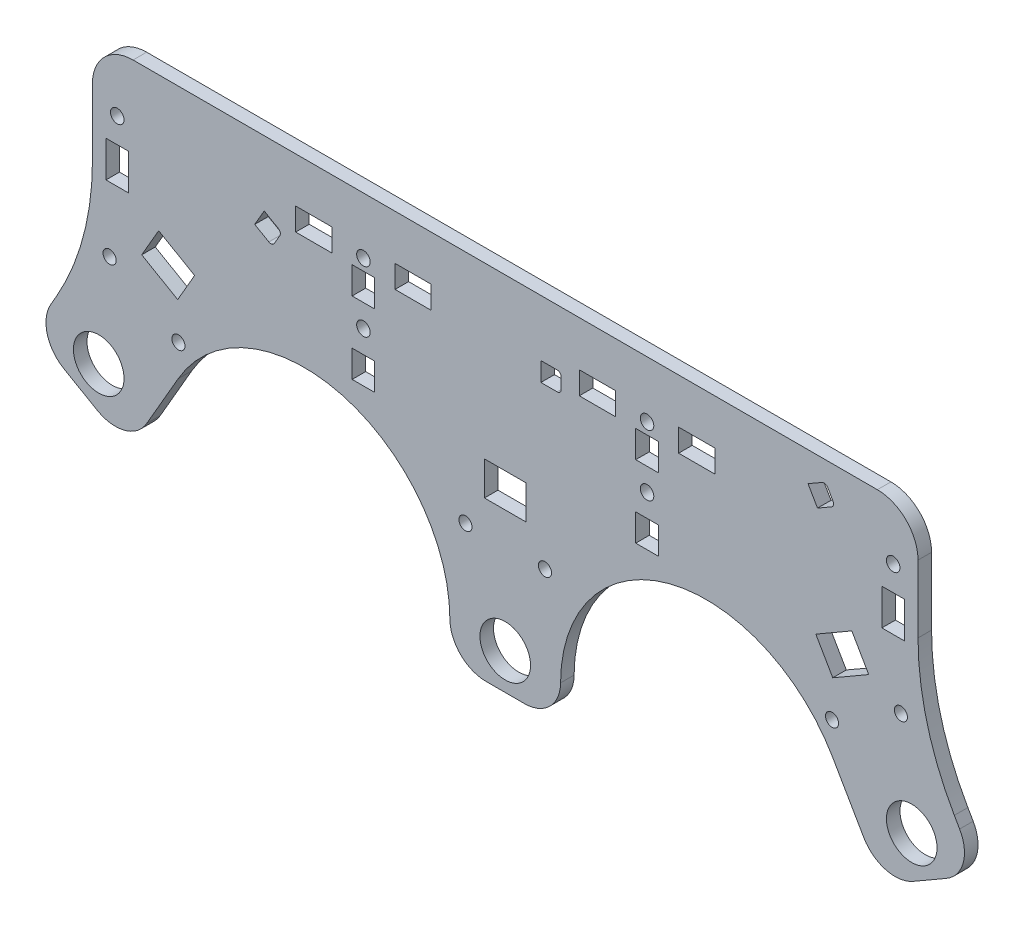
SolidWorks part; units mm, degrees
ref_plane "Front Plane" through (0, 0, 0) normal (0, 0, 1) x (1, 0, 0)
ref_plane "Top Plane" through (0, 0, 0) normal (0, 1, 0) x (1, 0, 0)
ref_plane "Right Plane" through (0, 0, 0) normal (1, 0, 0) x (0, 0, -1)
sketch "Sketch1" plane through (0, 0, 0) normal (0, 0, 1) x (1, 0, 0)
  line L0 (-12.25, 32.0854) -> (-12.25, -8)
  line L1 (-12.25, -8) -> (12.25, -8)
  line L2 (12.25, -8) -> (12.25, 32.0854)
  line L3 (12.25, 32.0854) -> (63.1039, 32.0854)
  line L4 (63.1039, 32.0854) -> (83.3912, -3.0532)
  line L5 (83.3912, -3.0532) -> (104.6088, 9.1968)
  line L6 (104.6088, 9.1968) -> (91.394, 32.0854)
  line L7 (91.394, 32.0854) -> (91.394, 72.0854)
  line L8 (91.394, 72.0854) -> (-91.394, 72.0854)
  line L9 (-91.394, 72.0854) -> (-91.394, 32.0854)
  line L10 (-91.394, 32.0854) -> (-104.6088, 9.1968)
  line L11 (-104.6088, 9.1968) -> (-83.3912, -3.0532)
  line L12 (-83.3912, -3.0532) -> (-63.1039, 32.0854)
  line L13 (-63.1039, 32.0854) -> (-12.25, 32.0854)
  line L14 (7.75, -12) -> (-7.75, -12) construction
  line L15 (102.7117, 3.4827) -> (89.2883, -4.2673) construction
  line L16 (-89.2883, -4.2673) -> (-102.7117, 3.4827) construction
  line L17 (-67.7572, 26.0256) -> (-84.5072, -2.9862) construction
  line L18 (-103.9928, 8.2638) -> (-87.2428, 37.2756) construction
  line L19 (87.2428, 37.2756) -> (103.9928, 8.2638) construction
  line L20 (84.5072, -2.9862) -> (67.7572, 26.0256) construction
  line L21 (11.25, 25) -> (11.25, -8.5) construction
  line L22 (-11.25, -8.5) -> (-11.25, 25) construction
  line L23 (-91.394, 32.0854) -> (-63.1039, 32.0854) construction
  line L24 (-12.25, 32.0854) -> (12.25, 32.0854) construction
  line L25 (63.1039, 32.0854) -> (91.394, 32.0854) construction
  line L26 (0, 72.0854) -> (0, -50.5753) construction
  circle A0 centre (0, 0) radius 33.5 construction
  circle A1 centre (-90, 10) radius 33.5 construction
  circle A2 centre (90, 10) radius 33.5 construction
  arc A3 (-72.4108, 15.9654) -> (-12.25, -0.1546) centre (-44.4901, -0.1546) cw
  arc A4 (72.4108, 15.9654) -> (12.25, -0.1546) centre (44.4901, -0.1546) ccw
  dimension "D10" = 67
  dimension "D11" = 40
  dimension "D1" = 4
  dimension "D2" = 4
  dimension "D3" = 4
  dimension "D4" = 1
  dimension "D5" = 1
  dimension "D6" = 1
  dimension "D7" = 1
  dimension "D8" = 1
  dimension "D9" = 1
extrude "Boss-Extrude1" add sketch "Sketch1" along normal blind 3 contours L12 L13 L0 L1 L2 L3 L4 L5 L6 L7 L8 L9 L10 L11 | L12 A3 L13 | L13 A3 L0 | A4 L3 L2 | A4 L4 L3
fillet "Fillet1" radius 60 2 edges at (91.394, 32.0854, 1.5) (-91.394, 32.0854, 1.5)
fillet "Fillet2" radius 8 6 edges at (-104.6088, 9.1968, 1.5) (-83.3912, -3.0532, 1.5) (-12.25, -8, 1.5) (12.25, -8, 1.5) (83.3912, -3.0532, 1.5) (104.6088, 9.1968, 1.5)
sketch "Sketch3" plane through (0, 0, 3) normal (0, 0, 1) x (1, 0, 0)
  line L8 (-53.3584, 57.6651) -> (-55.4584, 54.0278)
  line L9 (-55.4584, 54.0278) -> (-52.3407, 52.2278)
  line L10 (-51.1113, 52.5572) -> (-49.9113, 54.6357)
  line L11 (-50.2407, 55.8651) -> (-53.3584, 57.6651)
  line L12 (-53.3584, 57.6651) -> (-55.4584, 54.0278)
  line L13 (-55.4584, 54.0278) -> (-52.3407, 52.2278)
  line L14 (-51.1113, 52.5572) -> (-49.9113, 54.6357)
  line L15 (-50.2407, 55.8651) -> (-53.3584, 57.6651)
  line L16 (-68.7663, 37.5779) -> (-76.7337, 42.1779)
  line L17 (-76.7337, 42.1779) -> (-80.4837, 35.6827)
  line L18 (-80.4837, 35.6827) -> (-72.5163, 31.0827)
  line L19 (-72.5163, 31.0827) -> (-68.7663, 37.5779)
  line L20 (7.9, 59.6) -> (7.9, 55.4)
  line L21 (7.9, 55.4) -> (11.5, 55.4)
  line L22 (12.4, 56.3) -> (12.4, 58.7)
  line L23 (11.5, 59.6) -> (7.9, 59.6)
  line L24 (7.9, 59.6) -> (7.9, 55.4)
  line L25 (7.9, 55.4) -> (11.5, 55.4)
  line L26 (12.4, 56.3) -> (12.4, 58.7)
  line L27 (11.5, 59.6) -> (7.9, 59.6)
  line L32 (67.0416, 65.5651) -> (69.1416, 61.9278)
  line L33 (69.1416, 61.9278) -> (72.2593, 63.7278)
  line L34 (72.5887, 64.9572) -> (71.3887, 67.0357)
  line L35 (70.1593, 67.3651) -> (67.0416, 65.5651)
  line L36 (67.0416, 65.5651) -> (69.1416, 61.9278)
  line L37 (69.1416, 61.9278) -> (72.2593, 63.7278)
  line L38 (72.5887, 64.9572) -> (71.3887, 67.0357)
  line L39 (70.1593, 67.3651) -> (67.0416, 65.5651)
  line L40 (-68.7663, 37.5779) -> (-76.7337, 42.1779)
  line L41 (-76.7337, 42.1779) -> (-80.4837, 35.6827)
  line L42 (-80.4837, 35.6827) -> (-72.5163, 31.0827)
  line L43 (-72.5163, 31.0827) -> (-68.7663, 37.5779)
  line L48 (4.6, 34.5) -> (-4.6, 34.5)
  line L49 (-4.6, 34.5) -> (-4.6, 27)
  line L50 (-4.6, 27) -> (4.6, 27)
  line L51 (4.6, 27) -> (4.6, 34.5)
  line L52 (4.6, 34.5) -> (-4.6, 34.5)
  line L53 (-4.6, 34.5) -> (-4.6, 27)
  line L54 (-4.6, 27) -> (4.6, 27)
  line L55 (4.6, 27) -> (4.6, 34.5)
  line L60 (76.7337, 42.1779) -> (68.7663, 37.5779)
  line L61 (68.7663, 37.5779) -> (72.5163, 31.0827)
  line L62 (72.5163, 31.0827) -> (80.4837, 35.6827)
  line L63 (80.4837, 35.6827) -> (76.7337, 42.1779)
  line L64 (76.7337, 42.1779) -> (68.7663, 37.5779)
  line L65 (68.7663, 37.5779) -> (72.5163, 31.0827)
  line L66 (72.5163, 31.0827) -> (80.4837, 35.6827)
  line L67 (80.4837, 35.6827) -> (76.7337, 42.1779)
  circle A0 centre (87.596, 31.7638) radius 1.45 construction
  circle A1 centre (72.354, 22.9638) radius 1.45 construction
  circle A2 centre (8.8, 20.05) radius 1.45 construction
  circle A3 centre (-8.8, 20.05) radius 1.45 construction
  circle A4 centre (-87.596, 31.7638) radius 1.45 construction
  circle A5 centre (-72.354, 22.9638) radius 1.45 construction
  circle A6 centre (87.596, 31.7638) radius 1.45
  circle A7 centre (72.354, 22.9638) radius 1.45
  circle A8 centre (8.8, 20.05) radius 1.45
  circle A9 centre (-8.8, 20.05) radius 1.45
  circle A10 centre (-87.596, 31.7638) radius 1.45
  circle A11 centre (-72.354, 22.9638) radius 1.45
  circle A14 centre (-84.375, 19.7428) radius 3.45
  circle A15 centre (-84.375, 19.7428) radius 3.45 construction
  arc A16 (-52.3407, 52.2278) -> (-51.1113, 52.5572) centre (-51.8907, 53.0072) ccw
  arc A17 (-49.9113, 54.6357) -> (-50.2407, 55.8651) centre (-50.6907, 55.0857) ccw
  arc A18 (-52.3407, 52.2278) -> (-51.1113, 52.5572) centre (-51.8907, 53.0072) ccw
  arc A19 (-49.9113, 54.6357) -> (-50.2407, 55.8651) centre (-50.6907, 55.0857) ccw
  circle A21 centre (0, 11.25) radius 3.45
  arc A22 (11.5, 55.4) -> (12.4, 56.3) centre (11.5, 56.3) ccw
  arc A23 (12.4, 58.7) -> (11.5, 59.6) centre (11.5, 58.7) ccw
  arc A24 (11.5, 55.4) -> (12.4, 56.3) centre (11.5, 56.3) ccw
  arc A25 (12.4, 58.7) -> (11.5, 59.6) centre (11.5, 58.7) ccw
  circle A26 centre (0, 11.25) radius 3.45 construction
  arc A28 (72.2593, 63.7278) -> (72.5887, 64.9572) centre (71.8093, 64.5072) ccw
  arc A29 (71.3887, 67.0357) -> (70.1593, 67.3651) centre (70.6093, 66.5857) ccw
  arc A30 (72.2593, 63.7278) -> (72.5887, 64.9572) centre (71.8093, 64.5072) ccw
  arc A31 (71.3887, 67.0357) -> (70.1593, 67.3651) centre (70.6093, 66.5857) ccw
  circle A32 centre (84.375, 19.7428) radius 3.45
  circle A33 centre (84.375, 19.7428) radius 3.45 construction
  circle A35 centre (0, 0) radius 5.6
  circle A36 centre (0, 0) radius 5.6
  circle A38 centre (-90, 10) radius 5.6
  circle A39 centre (-90, 10) radius 5.6
  circle A41 centre (90, 10) radius 5.6
  circle A42 centre (90, 10) radius 5.6
  dimension "D1" = 0.1
  dimension "D2" = 0.1
  dimension "D3" = 0.1
  dimension "D4" = 2
  dimension "D5" = 2
  dimension "D6" = 2
  dimension "D7" = 1.5
  dimension "D8" = 1.5
  dimension "D9" = 1.5
  dimension "D10" = 2
  dimension "D11" = 2
  dimension "D12" = 2
extrude "Cut-Extrude1" cut sketch "Sketch3" against normal through all
sketch "Sketch4" plane through (0, 0, 3) normal (0, 0, 1) x (1, 0, 0)
  line L0 (84.394, 57.0854) -> (84.394, 62.0854) construction
  line L1 (29.894, 57.0854) -> (29.894, 62.0854) construction
  line L2 (32.894, 57.0854) -> (32.894, 62.0854) construction
  line L3 (87.394, 57.0854) -> (87.394, 62.0854) construction
  line L4 (-46.394, 62.0854) -> (-46.394, 57.0854)
  line L5 (-46.394, 57.0854) -> (-38.394, 57.0854)
  line L6 (-38.394, 57.0854) -> (-38.394, 62.0854)
  line L7 (-38.394, 62.0854) -> (-46.394, 62.0854)
  line L8 (-46.394, 62.0854) -> (-46.394, 57.0854)
  line L9 (-46.394, 57.0854) -> (-38.394, 57.0854)
  line L10 (-38.394, 57.0854) -> (-38.394, 62.0854)
  line L11 (-38.394, 62.0854) -> (-46.394, 62.0854)
  line L12 (-16.394, 57.0854) -> (-16.394, 62.0854)
  line L13 (-16.394, 62.0854) -> (-24.394, 62.0854)
  line L14 (-24.394, 62.0854) -> (-24.394, 57.0854)
  line L15 (-24.394, 57.0854) -> (-16.394, 57.0854)
  line L16 (-16.394, 57.0854) -> (-16.394, 62.0854)
  line L17 (-16.394, 62.0854) -> (-24.394, 62.0854)
  line L18 (-24.394, 62.0854) -> (-24.394, 57.0854)
  line L19 (-24.394, 57.0854) -> (-16.394, 57.0854)
  line L20 (16.394, 62.0854) -> (16.394, 57.0854)
  line L21 (16.394, 57.0854) -> (24.394, 57.0854)
  line L22 (24.394, 57.0854) -> (24.394, 62.0854)
  line L23 (24.394, 62.0854) -> (16.394, 62.0854)
  line L24 (16.394, 62.0854) -> (16.394, 57.0854)
  line L25 (16.394, 57.0854) -> (24.394, 57.0854)
  line L26 (24.394, 57.0854) -> (24.394, 62.0854)
  line L27 (24.394, 62.0854) -> (16.394, 62.0854)
  line L28 (46.394, 57.0854) -> (46.394, 62.0854)
  line L29 (46.394, 62.0854) -> (38.394, 62.0854)
  line L30 (38.394, 62.0854) -> (38.394, 57.0854)
  line L31 (38.394, 57.0854) -> (46.394, 57.0854)
  line L32 (46.394, 57.0854) -> (46.394, 62.0854)
  line L33 (46.394, 62.0854) -> (38.394, 62.0854)
  line L34 (38.394, 62.0854) -> (38.394, 57.0854)
  line L35 (38.394, 57.0854) -> (46.394, 57.0854)
  line L36 (-29.894, 57.0854) -> (-29.894, 62.0854) construction
  line L37 (-32.894, 57.0854) -> (-32.894, 62.0854) construction
  line L38 (-84.394, 57.0854) -> (-84.394, 62.0854) construction
  line L39 (-87.394, 57.0854) -> (-87.394, 62.0854) construction
  line L40 (-84.394, 57.0854) -> (-84.394, 62.0854) construction
  line L41 (-87.394, 57.0854) -> (-87.394, 62.0854) construction
  line L42 (84.394, 57.0854) -> (84.394, 62.0854) construction
  line L43 (-32.894, 57.0854) -> (-32.894, 62.0854) construction
  line L44 (-29.894, 57.0854) -> (-29.894, 62.0854) construction
  line L45 (87.394, 57.0854) -> (87.394, 62.0854) construction
  line L46 (32.894, 57.0854) -> (32.894, 62.0854) construction
  line L47 (29.894, 57.0854) -> (29.894, 62.0854) construction
  line L48 (-87.394, 59.5854) -> (-84.394, 59.5854) construction
  line L49 (-32.894, 59.5854) -> (-29.894, 59.5854) construction
  line L50 (29.894, 59.5854) -> (32.894, 59.5854) construction
  line L51 (84.394, 59.5854) -> (87.394, 59.5854) construction
  circle A0 centre (-31.394, 59.5854) radius 1.5
  circle A1 centre (31.394, 59.5854) radius 1.5
  circle A2 centre (-85.894, 59.5854) radius 1.5
  circle A3 centre (85.894, 59.5854) radius 1.5
  dimension "D1" = 0
  dimension "D2" = 0
  dimension "D3" = 0
  dimension "D4" = 0
extrude "Cut-Extrude2" cut sketch "Sketch4" against normal through all
sketch "Sketch5" plane through (0, 0, 3) normal (0, 0, 1) x (1, 0, 0)
  line L4 (-88.394, 54.0854) -> (-88.394, 46.0854)
  line L5 (-88.394, 46.0854) -> (-83.394, 46.0854)
  line L6 (-83.394, 46.0854) -> (-83.394, 54.0854)
  line L7 (-83.394, 54.0854) -> (-88.394, 54.0854)
  line L8 (-88.394, 54.0854) -> (-88.394, 46.0854)
  line L9 (-88.394, 46.0854) -> (-83.394, 46.0854)
  line L10 (-83.394, 46.0854) -> (-83.394, 54.0854)
  line L11 (-83.394, 54.0854) -> (-88.394, 54.0854)
  line L12 (88.394, 46.0854) -> (88.394, 54.0854)
  line L13 (88.394, 54.0854) -> (83.394, 54.0854)
  line L14 (83.394, 54.0854) -> (83.394, 46.0854)
  line L15 (83.394, 46.0854) -> (88.394, 46.0854)
  line L16 (88.394, 46.0854) -> (88.394, 54.0854)
  line L17 (88.394, 54.0854) -> (83.394, 54.0854)
  line L18 (83.394, 54.0854) -> (83.394, 46.0854)
  line L19 (83.394, 46.0854) -> (88.394, 46.0854)
  dimension "D1" = 0
  dimension "D2" = 0
extrude "Cut-Extrude3" cut sketch "Sketch5" against normal through all
fillet "Fillet3" radius 9 2 edges at (-91.394, 72.0854, 1.5) (91.394, 72.0854, 1.5)
sketch "Sketch6" plane through (0, 0, 3) normal (0, 0, 1) x (1, 0, 0)
  line L0 (-28.894, 44.5854) -> (-33.894, 44.5854) construction
  line L1 (-28.894, 47.5854) -> (-33.894, 47.5854) construction
  line L2 (28.894, 44.5854) -> (33.894, 44.5854) construction
  line L3 (28.894, 47.5854) -> (33.894, 47.5854) construction
  line L4 (33.894, 35.0854) -> (33.894, 41.0854)
  line L5 (33.894, 41.0854) -> (28.894, 41.0854)
  line L6 (28.894, 41.0854) -> (28.894, 35.0854)
  line L7 (28.894, 35.0854) -> (33.894, 35.0854)
  line L8 (33.894, 35.0854) -> (33.894, 41.0854)
  line L9 (33.894, 41.0854) -> (28.894, 41.0854)
  line L10 (28.894, 41.0854) -> (28.894, 35.0854)
  line L11 (28.894, 35.0854) -> (33.894, 35.0854)
  line L12 (33.894, 51.0854) -> (33.894, 57.0854)
  line L13 (33.894, 57.0854) -> (28.894, 57.0854)
  line L14 (28.894, 57.0854) -> (28.894, 51.0854)
  line L15 (28.894, 51.0854) -> (33.894, 51.0854)
  line L16 (33.894, 51.0854) -> (33.894, 57.0854)
  line L17 (33.894, 57.0854) -> (28.894, 57.0854)
  line L18 (28.894, 57.0854) -> (28.894, 51.0854)
  line L19 (28.894, 51.0854) -> (33.894, 51.0854)
  line L20 (-33.894, 57.0854) -> (-33.894, 51.0854)
  line L21 (-33.894, 51.0854) -> (-28.894, 51.0854)
  line L22 (-28.894, 51.0854) -> (-28.894, 57.0854)
  line L23 (-28.894, 57.0854) -> (-33.894, 57.0854)
  line L24 (-33.894, 57.0854) -> (-33.894, 51.0854)
  line L25 (-33.894, 51.0854) -> (-28.894, 51.0854)
  line L26 (-28.894, 51.0854) -> (-28.894, 57.0854)
  line L27 (-28.894, 57.0854) -> (-33.894, 57.0854)
  line L28 (-33.894, 41.0854) -> (-33.894, 35.0854)
  line L29 (-33.894, 35.0854) -> (-28.894, 35.0854)
  line L30 (-28.894, 35.0854) -> (-28.894, 41.0854)
  line L31 (-28.894, 41.0854) -> (-33.894, 41.0854)
  line L32 (-33.894, 41.0854) -> (-33.894, 35.0854)
  line L33 (-33.894, 35.0854) -> (-28.894, 35.0854)
  line L34 (-28.894, 35.0854) -> (-28.894, 41.0854)
  line L35 (-28.894, 41.0854) -> (-33.894, 41.0854)
  line L36 (-28.894, 44.5854) -> (-33.894, 44.5854) construction
  line L37 (-28.894, 47.5854) -> (-33.894, 47.5854) construction
  line L38 (28.894, 44.5854) -> (33.894, 44.5854) construction
  line L39 (28.894, 47.5854) -> (33.894, 47.5854) construction
  line L40 (-31.394, 44.5854) -> (-31.394, 47.5854) construction
  line L41 (31.394, 44.5854) -> (31.394, 47.5854) construction
  circle A0 centre (-31.394, 46.0854) radius 1.5
  circle A1 centre (31.394, 46.0854) radius 1.5
  dimension "D1" = 0
  dimension "D2" = 0
  dimension "D3" = 0
  dimension "D4" = 0
extrude "Cut-Extrude4" cut sketch "Sketch6" against normal through all
